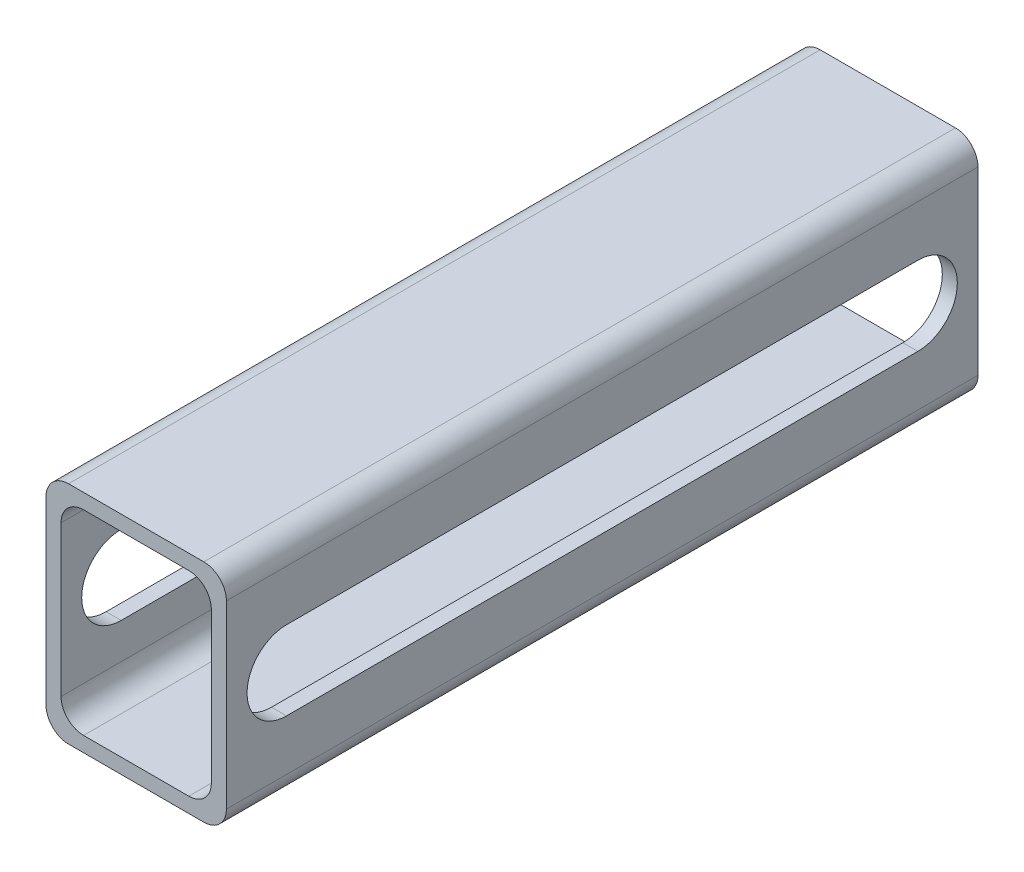
SolidWorks part; units mm, degrees
ref_plane "Plan de face" through (0, 0, 0) normal (0, 0, 1) x (1, 0, 0)
ref_plane "Plan de dessus" through (0, 0, 0) normal (0, 1, 0) x (1, 0, 0)
ref_plane "Plan de droite" through (0, 0, 0) normal (1, 0, 0) x (0, 0, -1)
sketch "Esquisse1" plane through (0, 0, 0) normal (0, 0, 1) x (1, 0, 0)
  line L1 (-9, -15) -> (9, -15)
  line L2 (-12, -12) -> (-12, 12)
  line L3 (-9, 15) -> (9, 15)
  line L4 (12, -12) -> (12, 12)
  line L5 (0, 15) -> (0, -15) construction
  line L6 (-12, 0) -> (12, 0) construction
  line L7 (-7, -13) -> (7, -13)
  line L8 (-10, -10) -> (-10, 10)
  line L9 (-7, 13) -> (7, 13)
  line L10 (10, -10) -> (10, 10)
  line L11 (0, 13) -> (0, -13) construction
  line L12 (-10, 0) -> (10, 0) construction
  arc A0 (7, -13) -> (10, -10) centre (7, -10) ccw
  arc A1 (9, -15) -> (12, -12) centre (9, -12) ccw
  arc A2 (-10, 10) -> (-7, 13) centre (-7, 10) cw
  arc A3 (-7, -13) -> (-10, -10) centre (-7, -10) cw
  arc A4 (7, 13) -> (10, 10) centre (7, 10) cw
  arc A5 (-12, 12) -> (-9, 15) centre (-9, 12) cw
  arc A6 (-9, -15) -> (-12, -12) centre (-9, -12) cw
  arc A7 (9, 15) -> (12, 12) centre (9, 12) cw
  point P0 (0, 0)
  point P4 (0, 0)
  point P13 (10, -13)
  point P19 (12, -15)
  point P22 (-10, 13)
  point P25 (-10, -13)
  point P30 (-12, 15)
  point P33 (-12, -15)
  dimension "D5" = 3
  dimension "D1" = 30
  dimension "D2" = 26
  dimension "D3" = 24
  dimension "D4" = 20
extrude "Boss.-Extru.1" add sketch "Esquisse1" against normal blind 100
sketch "Esquisse2" plane through (12, 0, 0) normal (1, 0, 0) x (0, 0, -1)
  line L0 (92, 0) -> (8, 0) construction
  line L1 (92, -5.25) -> (8, -5.25)
  line L2 (92, 5.25) -> (8, 5.25)
  line L3 (0, -12) -> (0, 12) construction
  line L4 (100, -12) -> (100, 12) construction
  arc A0 (92, -5.25) -> (92, 5.25) centre (92, 0) ccw
  arc A1 (8, 5.25) -> (8, -5.25) centre (8, 0) ccw
  point P3 (50, 0)
  dimension "D1" = 5.25
  dimension "D2" = 8
  dimension "D3" = 8
extrude "Enlèv. mat.-Extru.1" cut sketch "Esquisse2" against normal blind 36
